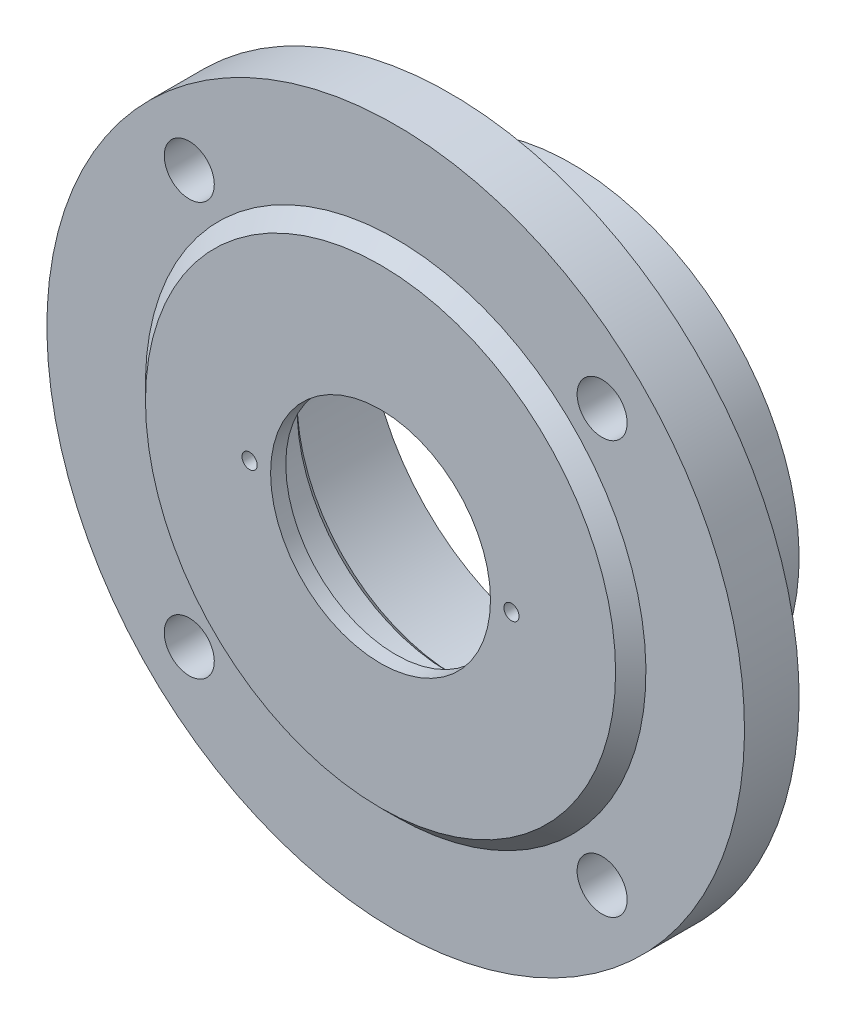
SolidWorks part; units mm, degrees
material "EN-GJL-300"
ref_plane "Front Plane" through (0, 0, 0) normal (0, 0, 1) x (1, 0, 0)
ref_plane "Top Plane" through (0, 0, 0) normal (0, 1, 0) x (1, 0, 0)
ref_plane "Right Plane" through (0, 0, 0) normal (1, 0, 0) x (0, 0, -1)
sketch "Sketch1" plane through (0, 0, 0) normal (1, 0, 0) x (0, 0, -1)
  line L0 (0, 14.5) -> (0, 31)
  line L1 (0, 31) -> (2, 33)
  line L2 (2, 33) -> (2, 46)
  line L3 (2, 46) -> (9.2, 46)
  line L4 (9.2, 46) -> (9.2, 31)
  line L5 (9.2, 31) -> (14.2, 31)
  line L7 (9, 20) -> (2, 20)
  line L8 (2, 20) -> (2, 14.5)
  line L9 (2, 14.5) -> (0, 14.5)
  line L10 (0, 0) -> (25.2, 0) construction
  line L12 (15.2, 30) -> (25.2, 30)
  line L14 (10, 21) -> (10, 26)
  line L15 (11, 27) -> (25.2, 27)
  line L16 (25.2, 27) -> (25.2, 30)
  line L17 (10, 21) -> (9, 20)
  arc A0 (14.2, 31) -> (15.2, 30) centre (15.2, 31) ccw
  arc A1 (10, 26) -> (11, 27) centre (11, 26) cw
  point P9 (10, 26)
  point P23 (12.6, 0)
  dimension "D11" = 1
  dimension "D16" = 46
  dimension "D13" = 1
  dimension "D2" = 14.5
  dimension "D3" = 5
  dimension "D4" = 7.2
  dimension "D5" = 27
  dimension "D6" = 2
  dimension "D7" = 2
  dimension "D8" = 2
  dimension "D9" = 20
  dimension "D10" = 7
  dimension "D12" = 1
  dimension "D14" = 1
  dimension "D15" = 31
  dimension "16" = 16
  dimension "D18" = 31
revolve "Revolve1" add sketch "Sketch1" angle 360 about L10
hole_wizard "M6 Clearance Hole1" positions "Sketch2" profile "Sketch3" hole size "M6" standard "ISO" end condition up to next
sketch "Sketch2" plane through (0, 0, -2) normal (0, 0, 1) x (1, 0, 0)
  line L0 (0, 38.5) -> (0, 0) construction
  line L2 (0, 0) -> (27.2236, 27.2236) construction
  circle A0 centre (0, 0) radius 38.5 construction
  point P0 (27.2236, 27.2236)
  dimension "D1" = 77
  dimension "D2" = 45
sketch "Sketch3" plane through (27.2236, 27.2236, -2) normal (1, 0, 0) x (0, -1, 0)
  line L0 (0, 0) -> (0, 7.2)
  line L1 (0, 7.2) -> (3.3, 7.2)
  line L2 (3.3, 7.2) -> (3.3, 0)
  line L5 (3.3, 0) -> (0, 0)
  line L11 (0, -6.35) -> (0, 107.95) construction
  dimension "Thru Hole Dia." = 6.6
  dimension "Thru Hole Depth" = 7.2
pattern_circular "CirPattern1" count 4 over 360 about axis through (0, 0, 0) along (0, 0, 1) of "M6 Clearance Hole1"
sketch "Sketch4" plane through (0, 0, -2) normal (0, 0, 1) x (1, 0, 0)
  line L0 (-27.2236, -27.2236) -> (27.2236, -27.2236) construction
sketch "Sketch5" plane through (0, 0, 0) normal (0, 0, 1) x (1, 0, 0)
  line L0 (0, 0) -> (0, 18.932) construction
  circle A0 centre (17.27, 0) radius 1
  circle A1 centre (-17.27, 0) radius 1
  dimension "D2" = 2
  dimension "D1" = 17.27
extrude "Cut-Extrude1" cut sketch "Sketch5" against normal up to next
equation "\"D.r\"= 52"
equation "\"d.e\"= 20"
equation "\"B.m\"= 7"
equation "\"D.m\"= 35"
